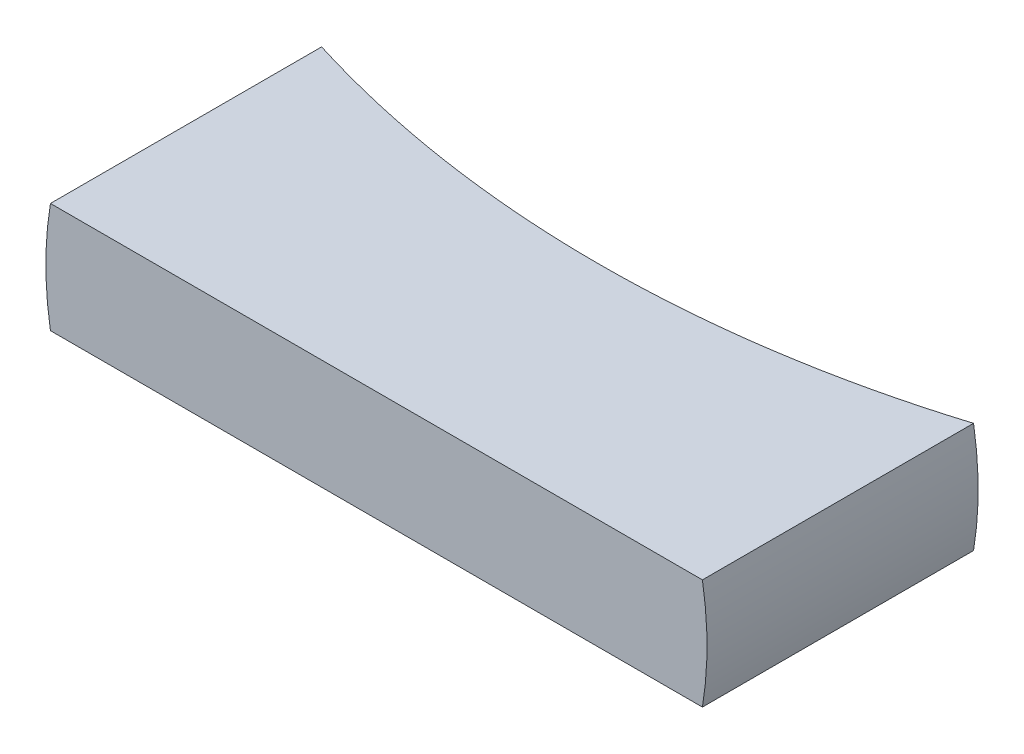
SolidWorks part; units mm, degrees
ref_plane "Front Plane" through (0, 0, 0) normal (0, 0, 1) x (1, 0, 0)
ref_plane "Top Plane" through (0, 0, 0) normal (0, 1, 0) x (1, 0, 0)
ref_plane "Right Plane" through (0, 0, 0) normal (1, 0, 0) x (0, 0, -1)
sketch "Sketch1" plane through (0, 0, 0) normal (0, 0, 1) x (1, 0, 0)
  circle A0 centre (0, 0) radius 3
extrude "Boss-Extrude1" add sketch "Sketch1" along normal blind 12 contours A0
sketch "Sketch3" plane through (0, 0, 0) normal (0, 1, 0) x (1, 0, 0)
  line L0 (0, -10.0001) -> (0, 10.0001)
  arc A0 (0, -10.0001) -> (0, 10.0001) centre (0, 0) cw
revolve "Cut-Revolve1" cut sketch "Sketch3" angle 360 about L0
sketch "Sketch4" plane through (0, 0, 0) normal (0, 0, 1) x (1, 0, 0)
  line L1 (8.7108, -0.5) -> (-8.7108, -0.5)
  line L2 (8.7108, -0.5) -> (8.7108, 0.5)
  line L3 (8.7108, 0.5) -> (-8.7108, 0.5)
  line L4 (-8.7108, -0.5) -> (-8.7108, 0.5)
  line L5 (8.7108, -0.5) -> (-8.7108, 0.5) construction
  line L6 (8.7108, 0.5) -> (-8.7108, -0.5) construction
  point P0 (0, 0)
extrude "Cut-Extrude1" cut sketch "Sketch4" against normal blind 20 and the other way blind 30 flip side to cut
